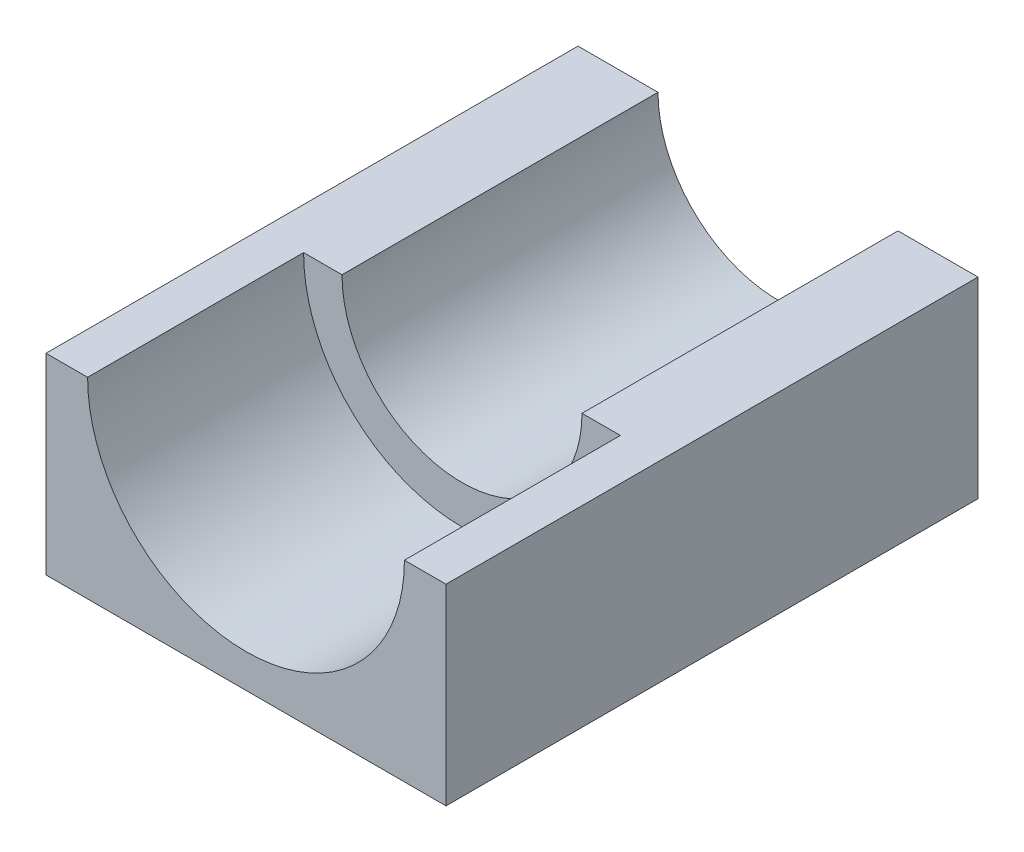
SolidWorks part; units mm, degrees
ref_plane "Front Plane" through (0, 0, 0) normal (0, 0, 1) x (1, 0, 0)
ref_plane "Top Plane" through (0, 0, 0) normal (0, 1, 0) x (1, 0, 0)
ref_plane "Right Plane" through (0, 0, 0) normal (1, 0, 0) x (0, 0, -1)
sketch "Sketch1" plane through (0, 0, 0) normal (0, 0, 1) x (1, 0, 0)
  line L2 (-20.582, -5.7024) -> (-20.582, 8.1505)
  line L3 (-20.582, 8.1505) -> (29.418, 8.1505)
  line L4 (29.418, -11.6495) -> (29.418, 8.1505)
  line L5 (-20.582, -5.7024) -> (29.418, 8.1505) construction
  line L6 (-20.582, 8.1505) -> (29.418, -11.6495) construction
  line L8 (-20.582, -5.7024) -> (-20.582, -15.8495)
  line L9 (-20.582, -15.8495) -> (29.418, -15.8495)
  line L10 (29.418, -11.6495) -> (29.418, -15.8495)
  point P0 (0, 0)
  dimension "D1" = 50
  dimension "D2" = 19.8
  dimension "D3" = 4.2
extrude "Boss-Extrude1" add sketch "Sketch1" against normal blind 66.5
sketch "Sketch4" plane through (0, 0, 0) normal (0, 0, 1) x (1, 0, 0)
  line L0 (29.418, 8.1505) -> (-20.582, 8.1505) construction
  circle A0 centre (4.418, 8.1505) radius 19.8
extrude "Cut-Extrude1" cut sketch "Sketch4" against normal blind 27
sketch "Sketch5" plane through (0, 0, -27) normal (0, 0, 1) x (1, 0, 0)
  line L0 (-15.382, 8.1505) -> (24.218, 8.1505) construction
  circle A0 centre (4.418, 8.1505) radius 15
extrude "Cut-Extrude2" cut sketch "Sketch5" against normal through all
sketch "Sketch6" plane through (0, 0, 0) normal (0, 0, 1) x (1, 0, 0)
  line L0 (4.418, -15.8495) -> (4.418, 28.9184) construction
  line L1 (-20.582, -15.8495) -> (29.418, -15.8495) construction
  line L2 (-15.382, 8.1505) -> (24.218, 8.1505) construction
  line L3 (-2.582, 8.1505) -> (-2.582, 28.9184) construction
  dimension "D1" = 7
